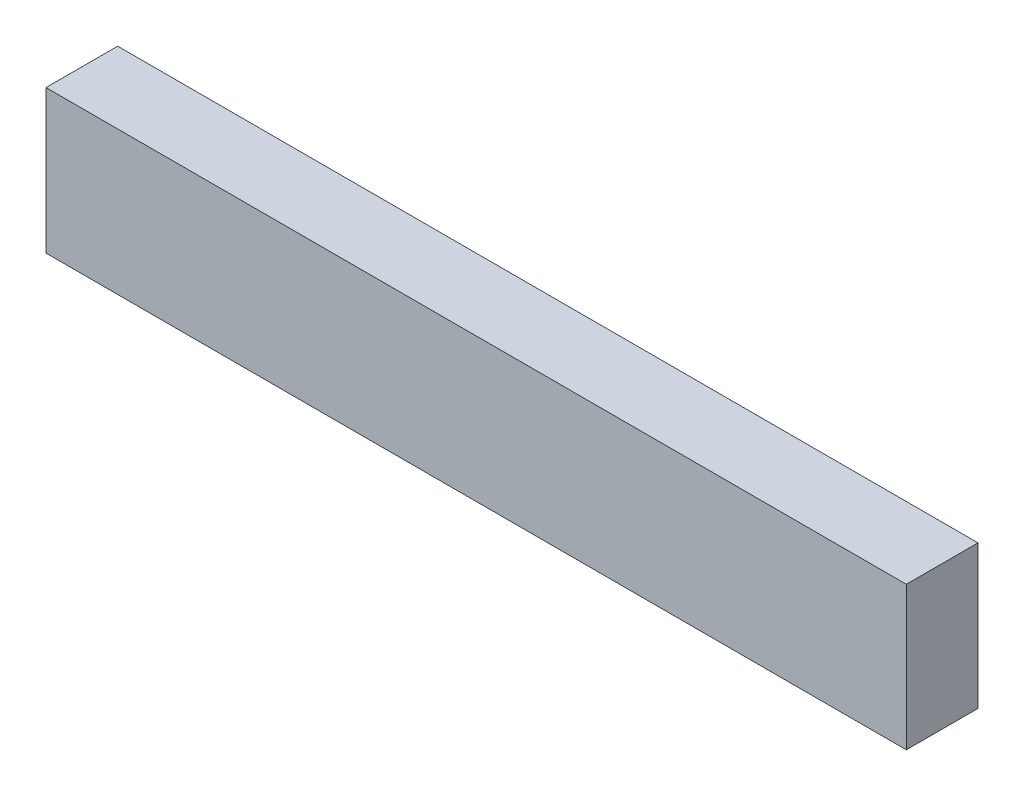
SolidWorks part; units mm, degrees
ref_plane "Front Plane" through (0, 0, 0) normal (0, 0, 1) x (1, 0, 0)
ref_plane "Top Plane" through (0, 0, 0) normal (0, 1, 0) x (1, 0, 0)
ref_plane "Right Plane" through (0, 0, 0) normal (1, 0, 0) x (0, 0, -1)
sketch "Sketch1" plane through (0, 0, 0) normal (0, 0, 1) x (1, 0, 0)
  line L1 (-304.8, -50.8) -> (304.8, -50.8)
  line L2 (-304.8, -50.8) -> (-304.8, 50.8)
  line L3 (-304.8, 50.8) -> (304.8, 50.8)
  line L4 (304.8, -50.8) -> (304.8, 50.8)
  line L5 (-304.8, -50.8) -> (304.8, 50.8) construction
  line L6 (-304.8, 50.8) -> (304.8, -50.8) construction
  point P0 (0, 0)
  dimension "D1" = 101.6
  dimension "D2" = 609.6
extrude "Boss-Extrude1" add sketch "Sketch1" along normal blind 50.8
